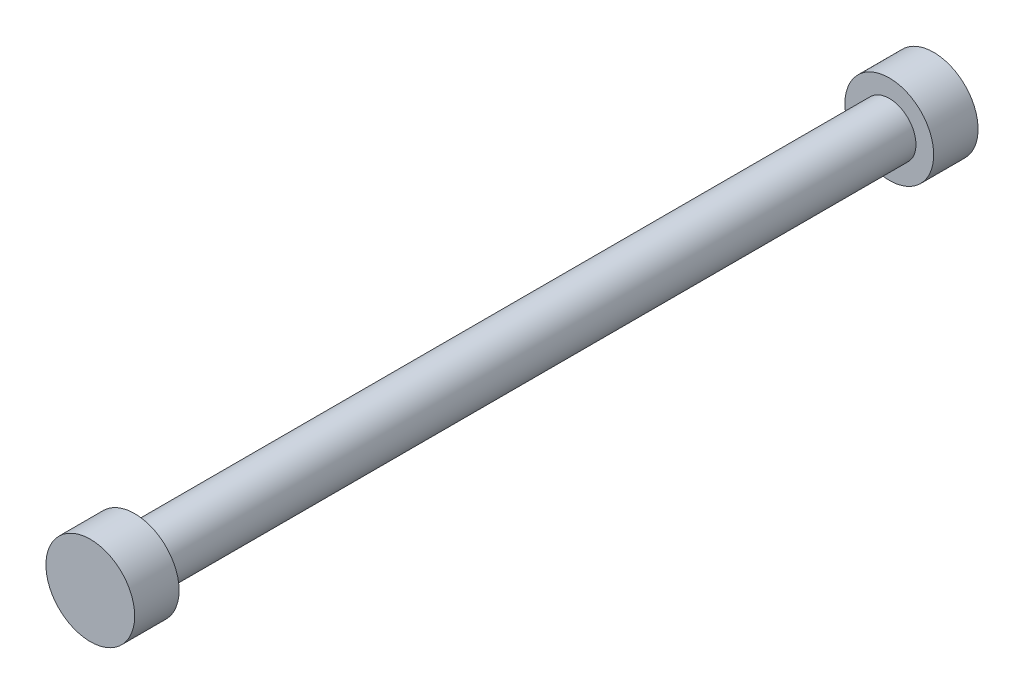
SolidWorks part; units mm, degrees
ref_plane "Ön Düzlem" through (0, 0, 0) normal (0, 0, 1) x (1, 0, 0)
ref_plane "Üst Düzlem" through (0, 0, 0) normal (0, 1, 0) x (1, 0, 0)
ref_plane "Sağ Düzlem" through (0, 0, 0) normal (1, 0, 0) x (0, 0, -1)
sketch "Çizim1" plane through (0, 0, 0) normal (0, 0, 1) x (1, 0, 0)
  circle A0 centre (-6.0711, 4.8302) radius 3
  dimension "D1" = 6
extrude "Yükseklik-Ekstrüzyon1" add sketch "Çizim1" along normal blind 85
sketch "Çizim2" plane through (0, 0, 0) normal (0, 0, -1) x (-1, 0, 0)
  circle A0 centre (6.0711, 4.8302) radius 5
  dimension "D1" = 10
extrude "Yükseklik-Ekstrüzyon2" add sketch "Çizim2" along normal blind 5
sketch "Çizim3" plane through (0, 0, 85) normal (0, 0, 1) x (1, 0, 0)
  circle A0 centre (-6.0711, 4.8302) radius 5
extrude "Yükseklik-Ekstrüzyon3" add sketch "Çizim3" along normal blind 5
